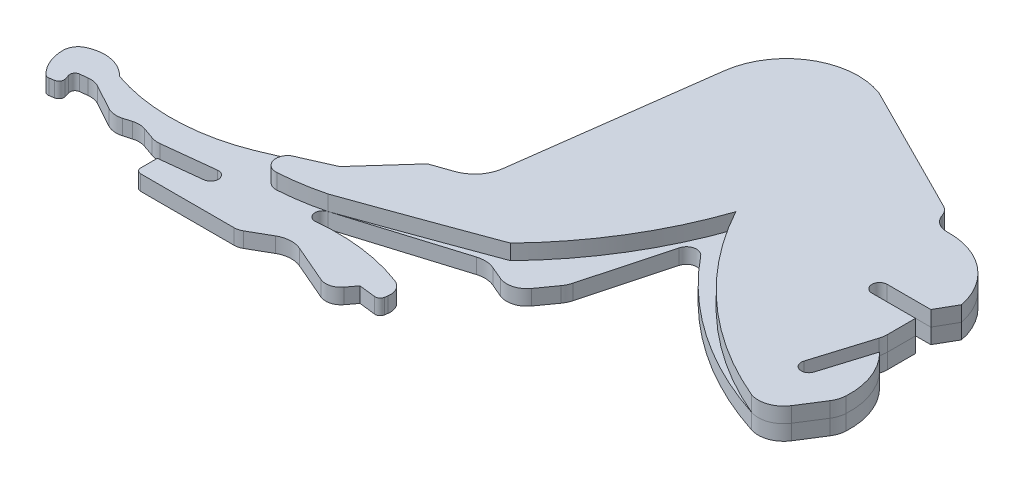
SolidWorks part; units mm, degrees
ref_plane "Front Plane" through (0, 0, 0) normal (0, 0, 1) x (1, 0, 0)
ref_plane "Top Plane" through (0, 0, 0) normal (0, 1, 0) x (1, 0, 0)
ref_plane "Right Plane" through (0, 0, 0) normal (1, 0, 0) x (0, 0, -1)
sketch "Sketch2" plane through (0, 0, 0) normal (0, 1, 0) x (1, 0, 0)
  line L0 (104.8617, 51.61) -> (96.2857, 51.61)
  line L1 (96.2857, 48.61) -> (104.8617, 48.61)
  line L2 (104.8617, 48.61) -> (104.8617, 42.36)
  line L3 (107.0706, 39.34) -> (104.0266, 29.4584)
  line L4 (101.1595, 30.3416) -> (104.8617, 42.36)
  line L5 (105.5312, 18.3607) -> (111.09, 27.1258)
  line L6 (104.8617, 51.61) -> (107.0706, 55.46)
  line L7 (89.7728, 69.8362) -> (57.4, 86.17)
  line L8 (41.6529, 73.6621) -> (36.03, 31.3784)
  line L9 (36.03, 31.3784) -> (29.1482, 28.9869)
  line L10 (29.1482, 28.9869) -> (21.9915, 21.0198)
  line L11 (21.9915, 21.0198) -> (8.1869, 15.1615)
  line L12 (0, 0) -> (0, 4.28)
  line L13 (0, 4.28) -> (8.2554, 5.2)
  line L14 (7.9231, 8.1815) -> (-3.1214, 6.9507)
  line L15 (-3.1214, 6.9507) -> (-7.4992, 8.4826)
  line L16 (-7.4992, 8.4826) -> (-11.8276, 7.2216)
  line L17 (-11.8276, 7.2216) -> (-19.2552, 11.2976)
  line L18 (-19.2552, 11.2976) -> (-23.2053, 10.8574)
  line L19 (-23.2053, 10.8574) -> (-22.2697, 7.6463)
  line L20 (-22.2697, 7.6463) -> (-24.8125, 7.2216)
  line L21 (0, 0) -> (20.16, 0)
  line L22 (20.16, 0) -> (27.0155, 3.9247)
  line L23 (27.0155, 3.9247) -> (38.9, -1.2)
  line L24 (38.9, -1.2) -> (41.66, 2.4827)
  line L25 (41.66, 2.4827) -> (45.9, 1.9915)
  line L26 (45.9, 1.9915) -> (46.4657, 5.8541)
  line L27 (25.83, 11.99) -> (49.95, 19.39)
  line L28 (49.95, 19.39) -> (57.13, 16.32)
  line L29 (57.13, 16.32) -> (61.9358, 23.0276)
  line L30 (61.9358, 23.0276) -> (67.6517, 44.29)
  arc A0 (96.2857, 51.61) -> (96.2857, 48.61) centre (96.2857, 50.11) ccw
  arc A1 (107.0706, 39.34) -> (111.09, 27.1258) centre (97.2099, 29.3266) cw
  arc A2 (104.0266, 29.4584) -> (101.1595, 30.3416) centre (102.5931, 29.9) cw
  arc A3 (107.0706, 55.46) -> (93.2591, 66.4439) centre (93.6334, 52.7391) ccw
  arc A4 (93.2591, 66.4439) -> (89.7728, 69.8362) centre (93.1665, 69.8362) cw
  arc A5 (57.4, 86.17) -> (41.6529, 73.6621) centre (56.0104, 71.7528) ccw
  arc A6 (8.1869, 15.1615) -> (-17.7049, 14.5311) centre (-5.6083, 49.7338) cw
  arc A7 (8.2554, 5.2) -> (7.9231, 8.1815) centre (8.0892, 6.6908) ccw
  arc A8 (-24.8125, 7.2216) -> (-27.5, 15.12) centre (-19.6156, 13.3963) cw
  arc A9 (-27.5, 15.12) -> (-17.7049, 14.5311) centre (-22.91, 9.71) cw
  arc A10 (46.4657, 5.8541) -> (26.4315, 9.0647) centre (30.5748, -29.1928) ccw
  arc A11 (26.4315, 9.0647) -> (25.83, 11.99) centre (26.27, 10.556) cw
  arc A12 (67.6517, 44.29) -> (105.5312, 18.3607) centre (122.4523, 83.7134) ccw
  point P4 (0, 0)
  point P9 (102.1515, 28.4665)
  point P12 (94.7857, 50.11)
  point P13 (-27.5, 15.12)
  point P72 (9.58, 6.8569)
  dimension "D6" = 1.5
  dimension "D11" = 1.5
  dimension "D32" = 14.0535
  dimension "D33" = 13.7098
  dimension "D34" = 3.3937
  dimension "D35" = 14.484
  dimension "D36" = 37.223
  dimension "D37" = 8.0706
  dimension "D38" = 7.0948
  dimension "D39" = 38.4812
  dimension "D40" = 67.5078
  dimension "D75" = 1.5
  dimension "D1" = 51.61
  dimension "D2" = 111.09
  dimension "D3" = 10.076
  dimension "D4" = 27.5
  dimension "D5" = 15.12
  dimension "D7" = 29.9
  dimension "D8" = 39.34
  dimension "D9" = 6.25
  dimension "D10" = 102.5931
  dimension "D12" = 4.28
  dimension "D13" = 20.16
  dimension "D14" = 5.14
  dimension "D15" = 1.2
  dimension "D16" = 45.9
  dimension "D17" = 38.9
  dimension "D18" = 86.17
  dimension "D19" = 9.58
  dimension "D20" = 5.2
  dimension "D21" = 11.99
  dimension "D22" = 16.32
  dimension "D23" = 57.13
  dimension "D24" = 49.95
  dimension "D25" = 26.27
  dimension "19.39" = 19.39
  dimension "D26" = 84.9
  dimension "D27" = 63.53
  dimension "D28" = 37.21
  dimension "D29" = 44.29
  dimension "D30" = 3.85
  dimension "D31" = 20
  dimension "D41" = 8.1869
  dimension "D42" = 21.9915
  dimension "D43" = 26.4315
  dimension "D44" = 27.0155
  dimension "D45" = 29.1482
  dimension "D46" = 41.6529
  dimension "D47" = 41.66
  dimension "D48" = 46.4657
  dimension "D49" = 56.0104
  dimension "D50" = 61.9358
  dimension "D51" = 67.6517
  dimension "D52" = 89.7728
  dimension "D53" = 97.2099
  dimension "D54" = 105.5312
  dimension "D55" = 122.4523
  dimension "D56" = 3.1214
  dimension "D57" = 5.6083
  dimension "D58" = 7.4992
  dimension "D59" = 11.8276
  dimension "D60" = 17.7049
  dimension "D61" = 19.2552
  dimension "D62" = 19.6156
  dimension "D63" = 22.2697
  dimension "D64" = 22.91
  dimension "D65" = 23.2053
  dimension "D66" = 24.8125
  dimension "D67" = 1.9915
  dimension "D68" = 2.4827
  dimension "D69" = 7.6463
  dimension "D70" = 8.4826
  dimension "D71" = 11.2976
  dimension "D72" = 21.0198
  dimension "D73" = 23.0276
  dimension "D74" = 28.9869
extrude "Boss-Extrude1" add sketch "Sketch2" along normal blind 3
fillet "Fillet1" radius 3 6 edges at (89.7728, 1.5, -69.8362) (29.1482, 1.5, -28.9869) (-27.5, 1.5, -15.12) (20.16, 1.5, 0) (46.4657, 1.5, -5.8541) (38.9, 1.5, 1.2)
fillet "Fillet2" radius 5 6 edges at (61.9358, 1.5, -23.0276) (49.95, 1.5, -19.39) (27.0155, 1.5, -3.9247) (104.8617, 1.5, -42.36) (111.09, 1.5, -27.1258) (105.5312, 1.5, -18.3607)
fillet "Fillet3" radius 4 6 edges at (36.03, 1.5, -31.3784) (-19.2552, 1.5, -11.2976) (-3.1214, 1.5, -6.9507) (-7.4992, 1.5, -8.4826) (-11.8276, 1.5, -7.2216) (57.13, 1.5, -16.32)
fillet "Fillet4" radius 1 5 edges at (45.9, 1.5, -1.9915) (0, 1.5, 0) (-24.8125, 1.5, -7.2216) (-22.2697, 1.5, -7.6463) (-23.2053, 1.5, -10.8574)
fillet "Fillet5" radius 10 1 edges at (57.4, 1.5, -86.17)
fillet "Fillet6" radius 2 1 edges at (67.6517, 1.5, -44.29)
sketch "Sketch3" plane through (0, 3, 0) normal (0, 1, 0) x (1, 0, 0)
  line L0 (104.8617, 48.61) -> (96.2857, 48.61) construction
  line L1 (96.2857, 51.61) -> (104.8617, 51.61) construction
  line L2 (104.8617, 48.61) -> (96.2857, 48.61)
  line L3 (96.2857, 51.61) -> (104.8617, 51.61)
  line L4 (107.0706, 39.34) -> (104.0266, 29.4584) construction
  line L5 (101.1595, 30.3416) -> (104.6402, 41.6407) construction
  line L6 (104.8617, 43.1127) -> (104.8617, 48.61) construction
  line L7 (107.0706, 39.34) -> (104.0266, 29.4584)
  line L8 (101.1595, 30.3416) -> (104.6402, 41.6407)
  line L9 (104.8617, 43.1127) -> (104.8617, 48.61)
  line L10 (104.8617, 51.61) -> (107.0706, 55.46) construction
  line L11 (104.8617, 51.61) -> (107.0706, 55.46)
  line L12 (88.4484, 70.5045) -> (59.5854, 85.0673) construction
  line L13 (88.4484, 70.5045) -> (62.8864, 83.4018)
  line L14 (107.5402, 21.5284) -> (110.4722, 26.1516) construction
  line L15 (107.5402, 21.5284) -> (110.4722, 26.1516)
  line L16 (15.7738, 14.9057) -> (22.3484, 17.8108)
  line L18 (0, 4.28) -> (0, 1) construction
  line L19 (30.4243, 26.8012) -> (23.7843, 19.4093)
  line L20 (30.526, 26.9143) -> (22.3484, 17.8108)
  line L22 (44.0418, 73.3444) -> (38.7437, 33.503)
  line L23 (43.8662, 72.0233) -> (38.7437, 33.503)
  line L118 (34.4938, 28.2932) -> (30.6696, 26.9642)
  line L119 (34.4938, 28.2932) -> (30.526, 26.9143)
  arc A0 (96.2857, 51.61) -> (96.2857, 48.61) centre (96.2857, 50.11) ccw construction
  arc A1 (96.2857, 51.61) -> (96.2857, 48.61) centre (96.2857, 50.11) ccw
  arc A2 (101.1595, 30.3416) -> (104.0266, 29.4584) centre (102.5931, 29.9) ccw construction
  arc A3 (104.6402, 41.6407) -> (104.8617, 43.1127) centre (99.8617, 43.1127) ccw construction
  arc A4 (101.1595, 30.3416) -> (104.0266, 29.4584) centre (102.5931, 29.9) ccw
  arc A5 (104.6402, 41.6407) -> (104.8617, 43.1127) centre (99.8617, 43.1127) ccw
  arc A6 (89.9449, 68.7693) -> (93.2591, 66.4439) centre (93.1665, 69.8362) ccw construction
  arc A7 (107.0706, 55.46) -> (93.2591, 66.4439) centre (93.6334, 52.7391) ccw construction
  arc A8 (89.9449, 68.7693) -> (93.2591, 66.4439) centre (93.1665, 69.8362) ccw
  arc A9 (107.0706, 55.46) -> (93.2591, 66.4439) centre (93.6334, 52.7391) ccw
  arc A10 (89.9449, 68.7693) -> (88.4484, 70.5045) centre (87.097, 67.8261) ccw construction
  arc A11 (89.9449, 68.7693) -> (88.4484, 70.5045) centre (87.097, 67.8261) ccw
  arc A12 (101.7871, 19.4463) -> (107.5402, 21.5284) centre (103.3177, 24.2063) ccw construction
  arc A13 (110.4722, 26.1516) -> (111.2422, 28.555) centre (106.2497, 28.8295) ccw construction
  arc A14 (111.2422, 28.555) -> (107.0706, 39.34) centre (97.2099, 29.3266) ccw construction
  arc A15 (101.7871, 19.4463) -> (107.5402, 21.5284) centre (103.3177, 24.2063) ccw
  arc A16 (110.4722, 26.1516) -> (111.2422, 28.555) centre (106.2497, 28.8295) ccw
  arc A17 (111.2422, 28.555) -> (107.0706, 39.34) centre (97.2099, 29.3266) ccw
  arc A18 (101.7871, 19.4463) -> (69.0141, 49.0865) centre (127.6835, 81.0185) cw
  arc A19 (69.0141, 49.0865) -> (52.2007, 21.5808) centre (-0.8104, 72.8763) cw
  arc A20 (25.83, 11.99) -> (52.2007, 21.5808) centre (-660.2111, 1939.3696) ccw
  arc A22 (17.1639, 10.6137) -> (15.7738, 14.9057) centre (17.0143, 12.9363) cw
  arc A23 (43.8662, 72.0233) -> (62.8864, 83.4018) centre (57.8959, 70.1576) cw
  arc A24 (25.83, 11.99) -> (17.1639, 10.6137) centre (14.1306, 57.6853) cw
  arc A140 (34.4938, 28.2932) -> (38.7437, 33.503) centre (32.3897, 34.348) ccw
  arc A141 (34.4938, 28.2932) -> (38.7437, 33.503) centre (32.3897, 34.348) ccw
  point P38 (69.0141, 49.0865)
  dimension "D5" = 66.7964
  dimension "D6" = 73.7659
  dimension "D7" = 2045.8359
  dimension "D8" = 2.3275
  dimension "D9" = 14.1532
  dimension "D10" = 47.1693
  dimension "D11" = 14.1306
  dimension "D12" = 15.7738
  dimension "D13" = 17.0143
  dimension "D14" = 43.8662
  dimension "D15" = 22.3484
  dimension "D16" = 52.2007
  dimension "D17" = 69.0141
  dimension "D18" = 127.6835
  dimension "D19" = 0.8104
  dimension "D1" = 2.41
  dimension "D2" = 2.41
  dimension "D3" = 2.41
  dimension "D4" = 2.41
extrude "Boss-Extrude2" add sketch "Sketch3" along normal blind 3 separate body
